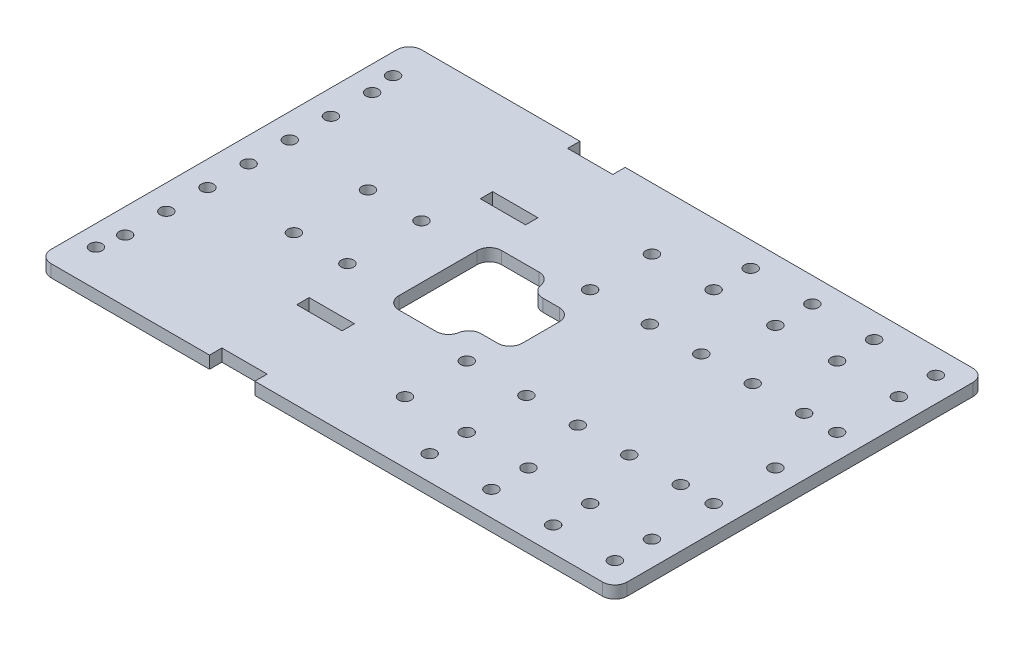
SolidWorks part; units mm, degrees
ref_plane "Front Plane" through (0, 0, 0) normal (0, 0, 1) x (1, 0, 0)
ref_plane "Top Plane" through (0, 0, 0) normal (0, 1, 0) x (1, 0, 0)
ref_plane "Right Plane" through (0, 0, 0) normal (1, 0, 0) x (0, 0, -1)
sketch "Sketch1" plane through (0, 0, 0) normal (0, 1, 0) x (1, 0, 0)
  line L1 (0, 0) -> (140, 0)
  line L2 (0, 0) -> (0, 90)
  line L3 (0, 90) -> (140, 90)
  line L4 (140, 0) -> (140, 90)
  dimension "D1" = 90
  dimension "D2" = 140
extrude "Plain Board" add sketch "Sketch1" along normal blind 3
sketch "Sketch2" plane through (0, 3, 0) normal (0, 1, 0) x (1, 0, 0)
  line L0 (0, 0) -> (140, 0) construction
  line L1 (41.5, 0) -> (52.5, 0)
  line L2 (41.5, 0) -> (41.5, 3)
  line L3 (41.5, 3) -> (52.5, 3)
  line L4 (52.5, 0) -> (52.5, 3)
  line L5 (0, 45) -> (39.6449, 45) construction
  line L6 (41.5, 21.2) -> (52.5, 21.2)
  line L7 (41.5, 21.2) -> (41.5, 24.2)
  line L8 (41.5, 24.2) -> (52.5, 24.2)
  line L9 (52.5, 21.2) -> (52.5, 24.2)
  line L10 (0, 90) -> (0, 0) construction
  line L11 (52.5, 68.8) -> (52.5, 65.8)
  line L12 (41.5, 65.8) -> (52.5, 65.8)
  line L13 (41.5, 68.8) -> (41.5, 65.8)
  line L14 (41.5, 68.8) -> (52.5, 68.8)
  line L15 (52.5, 90) -> (52.5, 87)
  line L16 (41.5, 87) -> (52.5, 87)
  line L17 (41.5, 90) -> (41.5, 87)
  line L18 (41.5, 90) -> (52.5, 90)
  dimension "D1" = 3
  dimension "D2" = 11
  dimension "D3" = 3
  dimension "D4" = 11
  dimension "D5" = 41.5
  dimension "D6" = 41.5
  dimension "D7" = 21.2
extrude "Motor Mount" cut sketch "Sketch2" against normal blind 3
sketch "Sketch3" plane through (0, 3, 0) normal (0, 1, 0) x (1, 0, 0)
  line L0 (140, 0) -> (140, 90) construction
  line L1 (140, 90) -> (52.5, 90) construction
  circle A0 centre (126, 60) radius 1.5
  circle A1 centre (113.5, 60) radius 1.5
  circle A2 centre (101, 60) radius 1.5
  circle A3 centre (88.5, 60) radius 1.5
  circle A4 centre (113.5, 30) radius 1.5
  circle A5 centre (101, 30) radius 1.5
  circle A6 centre (88.5, 30) radius 1.5
  circle A7 centre (126, 30) radius 1.5
  dimension "D1" = 3
  dimension "D2" = 14
  dimension "D3" = 30
  dimension "D4" = 4
  dimension "D5" = 2
extrude "Caster" cut sketch "Sketch3" against normal blind 3
sketch "Sketch4" plane through (0, 3, 0) normal (0, 1, 0) x (1, 0, 0)
  line L0 (0, 90) -> (0, 0) construction
  line L1 (0, 0) -> (41.5, 0) construction
  line L2 (0, 45) -> (23.6505, 45) construction
  circle A0 centre (5, 8.9) radius 1.5
  circle A1 centre (26, 36) radius 1.5
  circle A2 centre (39, 36) radius 1.5
  circle A3 centre (5, 81.1) radius 1.5
  circle A4 centre (39, 54) radius 1.5
  circle A5 centre (26, 54) radius 1.5
  dimension "D1" = 5
  dimension "D2" = 8.9
  dimension "D3" = 3
  dimension "D4" = 3
  dimension "D5" = 3
  dimension "D6" = 26
  dimension "D7" = 13
  dimension "D8" = 9
extrude "PCBs" cut sketch "Sketch4" against normal blind 3
sketch "Sketch5" plane through (0, 3, 0) normal (0, 1, 0) x (1, 0, 0)
  line L0 (0, 90) -> (0, 0) construction
  line L1 (52, 57.5) -> (67, 57.5)
  line L2 (52, 57.5) -> (52, 32.5)
  line L3 (52, 32.5) -> (67, 32.5)
  line L4 (67, 57.5) -> (67, 32.5)
  line L5 (67, 52.5) -> (77, 52.5)
  line L6 (67, 52.5) -> (67, 37.5)
  line L7 (67, 37.5) -> (77, 37.5)
  line L8 (77, 52.5) -> (77, 37.5)
  point P10 (0, 45)
  dimension "D1" = 52
  dimension "D2" = 15
  dimension "D3" = 10
  dimension "D4" = 25
  dimension "D5" = 15
  dimension "D6" = 5
  dimension "D7" = 12.5
extrude "Cable Hole" cut sketch "Sketch5" against normal blind 3 contours L8 L5 L4 L7 | L4 L1 L2 L3
sketch "Sketch6" plane through (0, 3, 0) normal (0, 1, 0) x (1, 0, 0)
  line L0 (140, 0) -> (140, 90) construction
  circle A0 centre (134, 15) radius 1.5
  circle A1 centre (119, 15) radius 1.5
  circle A2 centre (104, 15) radius 1.5
  circle A3 centre (89, 15) radius 1.5
  circle A4 centre (119, 75) radius 1.5
  circle A5 centre (104, 75) radius 1.5
  circle A6 centre (89, 75) radius 1.5
  circle A7 centre (134, 75) radius 1.5
  point P4 (140, 45)
  dimension "D1" = 3
  dimension "D2" = 6
  dimension "D3" = 30
  dimension "D4" = 4
  dimension "D5" = 2
extrude "Servo Board " cut sketch "Sketch6" against normal blind 3
sketch "Sketch7" plane through (0, 3, 0) normal (0, 1, 0) x (1, 0, 0)
  line L0 (140, 0) -> (140, 90) construction
  line L1 (52.5, 0) -> (140, 0) construction
  line L2 (0, 90) -> (0, 0) construction
  line L3 (0, 0) -> (41.5, 0) construction
  line L4 (140, 45) -> (36.4982, 45) construction
  circle A0 centre (134, 45) radius 1.5
  circle A1 centre (134, 6) radius 1.5
  circle A2 centre (119, 6) radius 1.5
  circle A3 centre (104, 6) radius 1.5
  circle A4 centre (89, 6) radius 1.5
  circle A5 centre (134, 60) radius 1.5
  circle A6 centre (134, 30) radius 1.5
  circle A7 centre (6, 45) radius 1.5
  circle A8 centre (6, 35) radius 1.5
  circle A9 centre (6, 25) radius 1.5
  circle A10 centre (6, 15) radius 1.5
  circle A13 centre (89, 84) radius 1.5
  circle A14 centre (104, 84) radius 1.5
  circle A15 centre (119, 84) radius 1.5
  circle A16 centre (134, 84) radius 1.5
  circle A17 centre (6, 75) radius 1.5
  circle A18 centre (6, 65) radius 1.5
  circle A19 centre (6, 55) radius 1.5
  point P2 (140, 45)
  dimension "D1" = 3
  dimension "D2" = 6
  dimension "D3" = 3
  dimension "D4" = 6
  dimension "D5" = 6
  dimension "D6" = 45
  dimension "D9" = 6
  dimension "D10" = 45
  dimension "D11" = 3
  dimension "D13" = 3
  dimension "D8" = 6
  dimension "D14" = 15
  dimension "D7" = 4
  dimension "D12" = 4
extrude "Sensor Holes" cut sketch "Sketch7" against normal blind 3
sketch "Sketch8" plane through (0, 3, 0) normal (0, 1, 0) x (1, 0, 0)
  line L0 (140, 0) -> (140, 90) construction
  line L1 (0, 45) -> (21.3194, 45) construction
  line L2 (0, 90) -> (0, 0) construction
  circle A0 centre (74, 60) radius 1.5
  circle A2 centre (134, 60) radius 1.5 construction
  circle A3 centre (74, 75) radius 1.5
  circle A4 centre (74, 15) radius 1.5
  circle A5 centre (74, 30) radius 1.5
  point P7 (140, 45)
  dimension "D1" = 60
  dimension "D2" = 3
  dimension "D3" = 15
  dimension "D4" = 2
extrude "Servo Board(2)" cut sketch "Sketch8" against normal blind 3
fillet "Fillet1" radius 3 7 edges at (0, 1.5, -90) (52, 1.5, -32.5) (52, 1.5, -57.5) (77, 1.5, -37.5) (67, 1.5, -37.5) (77, 1.5, -52.5) (67, 1.5, -52.5)
fillet "Fillet3" radius 3 5 edges at (140, 1.5, -90) (140, 1.5, 0) (0, 1.5, 0) (67, 1.5, -57.5) (67, 1.5, -32.5)
